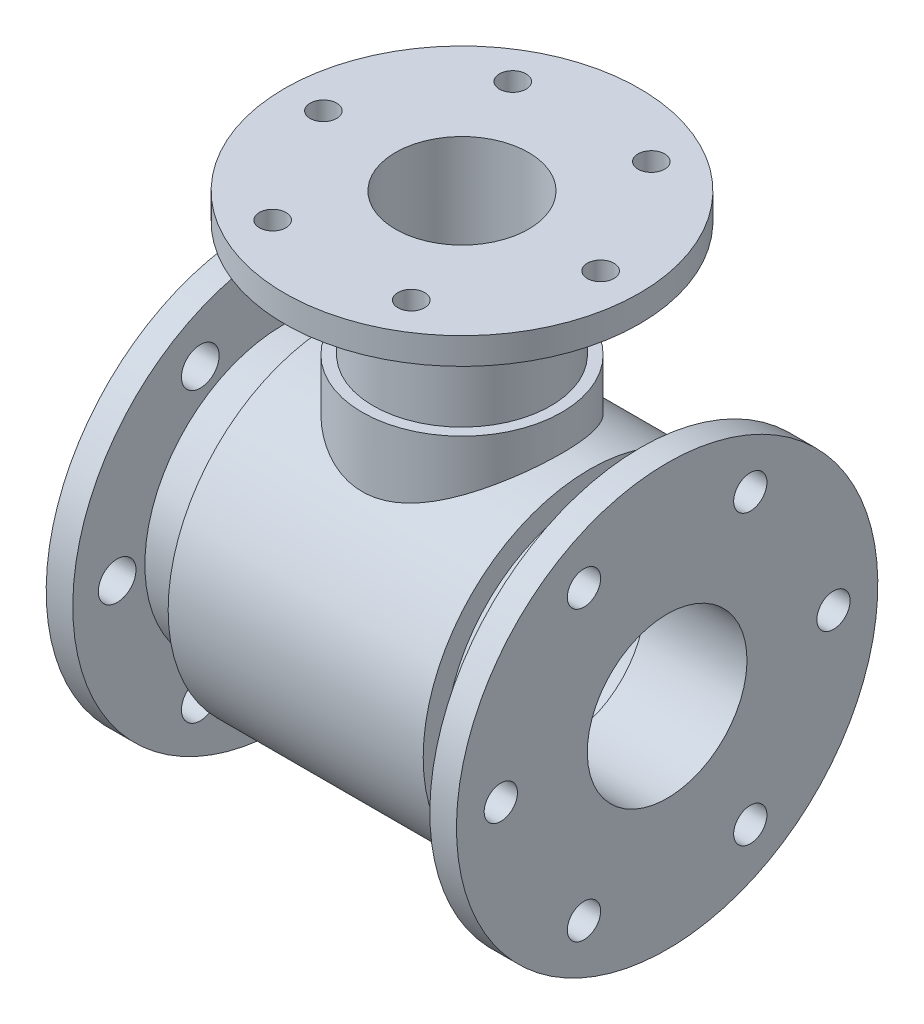
SolidWorks part; units mm, degrees
ref_plane "Front Plane" through (0, 0, 0) normal (0, 0, 1) x (1, 0, 0)
ref_plane "Top Plane" through (0, 0, 0) normal (0, 1, 0) x (1, 0, 0)
ref_plane "Right Plane" through (0, 0, 0) normal (1, 0, 0) x (0, 0, -1)
sketch "Sketch1" plane through (0, 0, 0) normal (0, 0, 1) x (1, 0, 0)
  line L0 (0, 0) -> (0, -154868.8461) construction
  line L1 (0, 0) -> (-154868.8461, 0) construction
  line L2 (-92.5, -95) -> (-92.5, -52.5)
  line L3 (-92.5, -52.5) -> (-87.5, -52.5)
  line L4 (-87.5, -52.5) -> (-87.5, -47.5)
  line L8 (29.5, -50.5) -> (29.5, -43.5)
  line L9 (29.5, -43.5) -> (44.5, -43.5)
  line L10 (46.5, -41.5) -> (46.5, -36)
  line L11 (46.5, -36) -> (92.5, -36)
  line L12 (92.5, -36) -> (92.5, -95)
  line L13 (92.5, -95) -> (80.5, -95)
  line L14 (80.5, -95) -> (80.5, -50)
  line L15 (80.5, -50) -> (66.5, -50)
  line L16 (66.5, -50) -> (66.5, -65)
  line L17 (66.5, -65) -> (57.5, -65)
  line L18 (57.5, -65) -> (57.5, -75)
  line L19 (57.5, -75) -> (-57.5, -75)
  line L20 (-57.5, -75) -> (-57.5, -62.5)
  line L21 (-57.5, -62.5) -> (-80.5, -62.5)
  line L22 (-80.5, -62.5) -> (-80.5, -95)
  line L23 (-80.5, -95) -> (-92.5, -95)
  line L24 (-87.5, -47.5) -> (-42.5, -47.5)
  line L25 (27.5, -52.5) -> (-40.5, -52.5)
  line L26 (-42.5, -50.5) -> (-42.5, -47.5)
  line L27 (44.5, -43.5) -> (46.5, -41.5)
  arc A0 (27.5, -52.5) -> (29.5, -50.5) centre (27.5, -50.5) ccw
  arc A1 (-40.5, -52.5) -> (-42.5, -50.5) centre (-40.5, -50.5) cw
  point P14 (46.5, -43.5)
  point P31 (-42.5, -52.5)
  dimension "D19" = 2
  dimension "D1" = 72
  dimension "D2" = 87
  dimension "D3" = 100
  dimension "D4" = 130
  dimension "D5" = 12
  dimension "D6" = 185
  dimension "D7" = 26
  dimension "D8" = 46
  dimension "D9" = 63
  dimension "D10" = 190
  dimension "D11" = 150
  dimension "D12" = 135
  dimension "D13" = 150
  dimension "D14" = 95
  dimension "D15" = 105
  dimension "D16" = 125
  dimension "D17" = 5
  dimension "D18" = 105
  dimension "D20" = 2
  dimension "D21" = 45
  dimension "D22" = 2
revolve "Revolve1" add sketch "Sketch1" angle 360 about L1
sketch "Sketch2" plane through (0, 0, 0) normal (0, 0, 1) x (1, 0, 0)
  line L0 (0, 0) -> (-50000, 0) construction
  line L1 (0, 0) -> (0, -50000) construction
  line L2 (0, 155) -> (80, 155)
  line L3 (80, 155) -> (80, 143)
  line L4 (80, 143) -> (40, 143)
  line L5 (40, 143) -> (40, 91)
  line L6 (40, 91) -> (45, 91)
  line L7 (45, 91) -> (45, 75)
  line L8 (57.5, 75) -> (-57.5, 75) construction
  line L9 (0, 155) -> (0, 75)
  line L10 (0, 75) -> (45, 75)
  dimension "D1" = 155
  dimension "D2" = 12
  dimension "D3" = 160
  dimension "D4" = 80
  dimension "D5" = 90
  dimension "D6" = 64
revolve "Revolve2" add sketch "Sketch2" angle 360 about L9
sketch "Sketch5" plane through (0, 75, 0) normal (0, -1, 0) x (1, 0, 0)
  circle A1 centre (0, 0) radius 45
  circle A2 centre (0, 0) radius 45
  dimension "D1" = 0
sketch "Sketch7" plane through (0, 75, 0) normal (0, -1, 0) x (1, 0, 0)
  circle A1 centre (0, 0) radius 45
  circle A2 centre (0, 0) radius 45
  dimension "D1" = 0
extrude "Boss-Extrude7" add sketch "Sketch7" along normal up to surface contours A2 up to face at (57.5, 75, 0)
sketch "Sketch15" plane through (0, 155, 0) normal (0, 1, 0) x (1, 0, 0)
  circle A0 centre (0, 0) radius 30
  dimension "D1" = 60
extrude "Cut-Extrude1" cut sketch "Sketch15" against normal up to next
sketch "Sketch16" plane through (92.5, 0, 0) normal (1, 0, 0) x (0, 0, -1)
  circle A0 centre (0, 0) radius 75 construction
  circle A1 centre (75, 0) radius 7.5
  circle A2 centre (37.5, -64.9519) radius 7.5
  circle A3 centre (-37.5, -64.9519) radius 7.5
  circle A4 centre (-75, 0) radius 7.5
  circle A5 centre (-37.5, 64.9519) radius 7.5
  circle A6 centre (37.5, 64.9519) radius 7.5
  point P30 (0, 0)
  dimension "D1" = 150
  dimension "D2" = 15
  dimension "D3" = 6
extrude "Cut-Extrude2" cut sketch "Sketch16" against normal up to next
sketch "Sketch21" plane through (-92.5, 0, 0) normal (-1, 0, 0) x (0, 0, 1)
  circle A0 centre (0, 0) radius 75 construction
  circle A1 centre (75, 0) radius 8.5
  circle A2 centre (37.5, -64.9519) radius 8.5
  circle A3 centre (-37.5, -64.9519) radius 8.5
  circle A4 centre (-75, 0) radius 8.5
  circle A5 centre (-37.5, 64.9519) radius 8.5
  circle A6 centre (37.5, 64.9519) radius 8.5
  point P30 (0, 0)
  dimension "D1" = 150
  dimension "D2" = 17
  dimension "D3" = 6
  dimension "D4" = 75
extrude "Cut-Extrude3" cut sketch "Sketch21" against normal up to next
sketch "Sketch25" plane through (0, 155, 0) normal (0, 1, 0) x (1, 0, 0)
  circle A0 centre (0, 0) radius 62.5 construction
  circle A1 centre (62.5, 0) radius 6
  circle A2 centre (31.25, -54.1266) radius 6
  circle A3 centre (-31.25, -54.1266) radius 6
  circle A4 centre (-62.5, 0) radius 6
  circle A5 centre (-31.25, 54.1266) radius 6
  circle A6 centre (31.25, 54.1266) radius 6
  point P5 (0, 0)
  point P6 (0, 0)
  point P17 (0, 0)
  dimension "D1" = 125
  dimension "D2" = 12
  dimension "D3" = 6
extrude "Cut-Extrude4" cut sketch "Sketch25" against normal up to next
